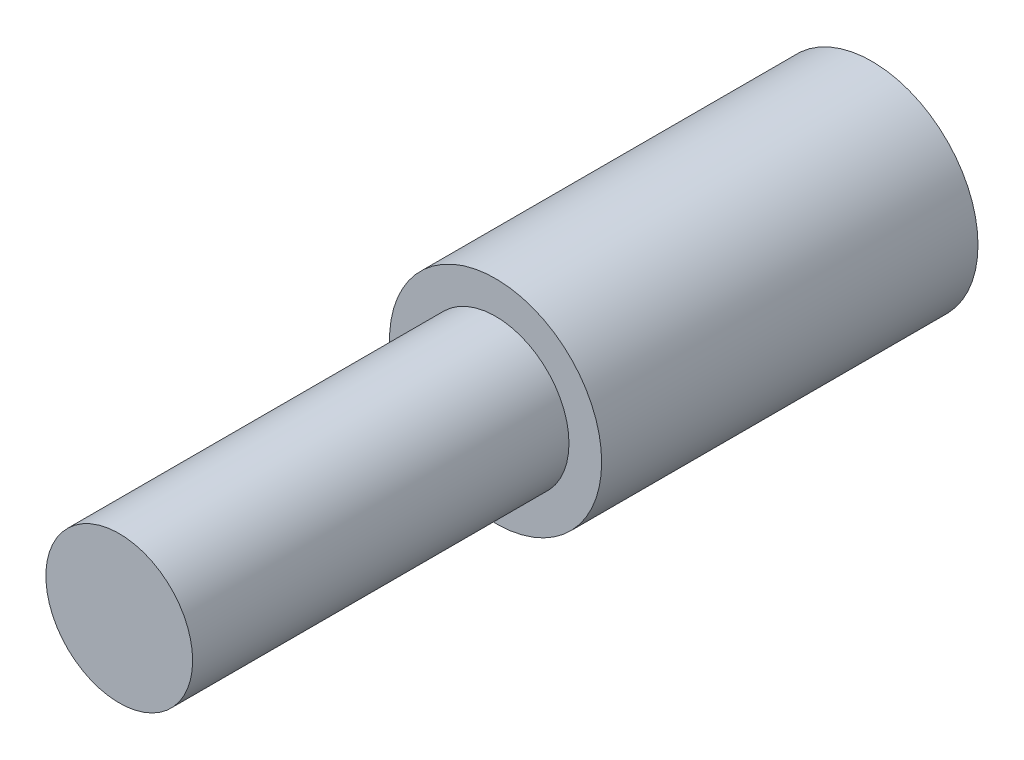
SolidWorks part; units mm, degrees
ref_plane "정면" through (0, 0, 0) normal (0, 0, 1) x (1, 0, 0)
ref_plane "윗면" through (0, 0, 0) normal (0, 1, 0) x (1, 0, 0)
ref_plane "우측면" through (0, 0, 0) normal (1, 0, 0) x (0, 0, -1)
sketch "스케치1" plane through (0, 0, 0) normal (0, 0, 1) x (1, 0, 0)
  circle A1 centre (0, 0) radius 3.9
  dimension "D1" = 7.8
extrude "보스-돌출1" add sketch "스케치1" along normal blind 20
sketch "스케치2" plane through (0, 0, 0) normal (0, 0, 1) x (1, 0, 0)
  circle A0 centre (0, 0) radius 5.6368
  circle A1 centre (0, 0) radius 2.6512
extrude "보스-돌출2" add sketch "스케치2" against normal blind 20
